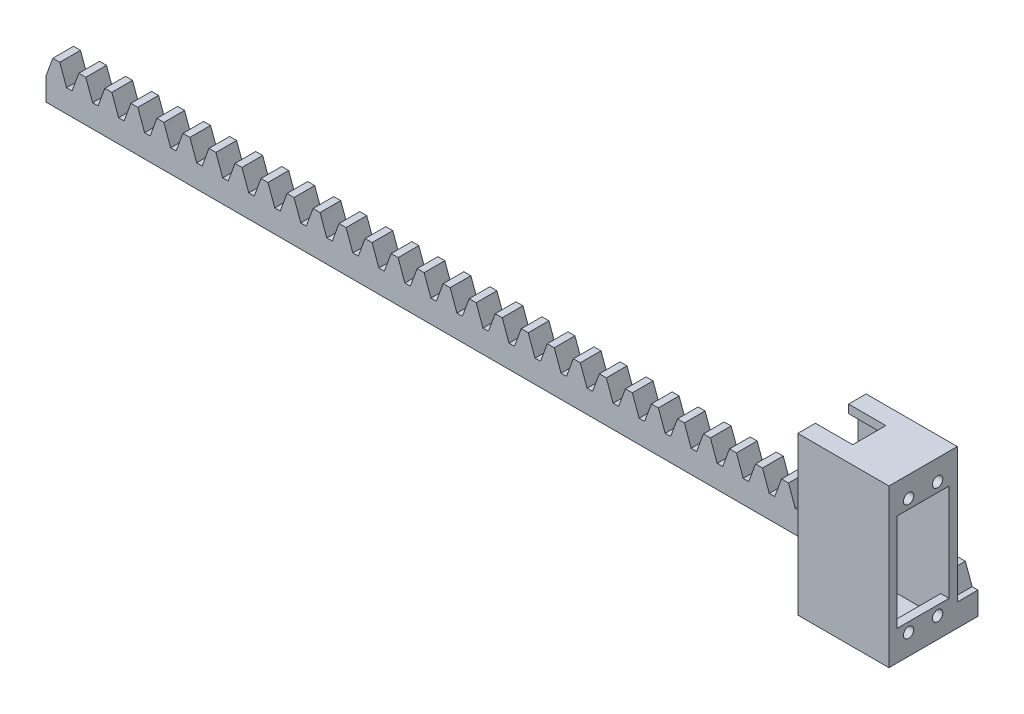
SolidWorks part; units mm, degrees
ref_plane "前视基准面" through (0, 0, 0) normal (0, 0, 1) x (1, 0, 0)
ref_plane "上视基准面" through (0, 0, 0) normal (0, 1, 0) x (1, 0, 0)
ref_plane "右视基准面" through (0, 0, 0) normal (1, 0, 0) x (0, 0, -1)
sketch "草图1" plane through (0, 0, 0) normal (0, 0, 1) x (1, 0, 0)
  line L1 (0, 0) -> (220, 0)
  line L2 (0, 0) -> (0, -5.5)
  line L3 (0, -5.5) -> (220, -5.5)
  line L4 (220, 0) -> (220, -5.5)
  dimension "D1" = 5.5
  dimension "L" = 220
extrude "拉伸1" add sketch "草图1" along normal blind 5
sketch "草图2" plane through (0, 0, 5) normal (0, 0, 1) x (1, 0, 0)
  line L0 (0, 0) -> (1.6379, 4.5)
  line L1 (1.6379, 4.5) -> (3.3236, 4.5)
  line L2 (3.3236, 4.5) -> (4.9614, 0)
  line L3 (220, 0) -> (0, 0) construction
  line L4 (0, 0) -> (4.9614, 0)
  line L5 (0.9099, 2.5) -> (4.0515, 2.5) construction
  dimension "D2" = 70
  dimension "alpha" = 110
  dimension "ha" = 2
  dimension "hf" = 2.5
  dimension "S" = 3.1416
extrude "拉伸2" add sketch "草图2" against normal up to surface (5 mm away) up to face at (110, -2.75, 0)
pattern_linear "阵列(线性)1" count 35 spacing 6.2832 along (1, 0, 0) of "拉伸2"
sketch "草图4" plane through (220, 0, 0) normal (1, 0, 0) x (0, 0, -1)
  line L0 (-5, -5.5) -> (-5, 0) construction
  line L1 (-5, -5.5) -> (-21.5, -5.5)
  line L2 (-5, -5.5) -> (-5, 32.5)
  line L3 (-5, 32.5) -> (-21.5, 32.5)
  line L4 (-21.5, -5.5) -> (-21.5, 32.5)
  line L6 (-21.5, 13.5) -> (-5, 13.5) construction
  line L7 (-13.25, 32.5) -> (-13.25, -5.5) construction
  line L8 (-5, -5.5) -> (0, -5.5) construction
  line L9 (-19.5, 25.25) -> (-7, 25.25)
  line L10 (-19.5, 25.25) -> (-19.5, 1.75)
  line L11 (-19.5, 1.75) -> (-7, 1.75)
  line L12 (-7, 25.25) -> (-7, 1.75)
  circle A0 centre (-16.75, 27.5) radius 1.25
  circle A1 centre (-9.75, 27.5) radius 1.25
  circle A2 centre (-9.75, -0.5) radius 1.25
  circle A3 centre (-16.75, -0.5) radius 1.25
  point P26 (-13.25, 25.25)
  point P27 (-7, 13.5)
  dimension "D3" = 2.5
  dimension "D4" = 7
  dimension "D5" = 28
  dimension "D1" = 16.5
  dimension "D2" = 38
  dimension "D6" = 23.5
  dimension "D7" = 12.5
extrude "凸台-拉伸1" add sketch "草图4" against normal blind 22
sketch "草图5" plane through (198, 0, 0) normal (-1, 0, 0) x (0, 0, 1)
  line L0 (7, 1.75) -> (7, 25.25) construction
  line L1 (7, 30.5) -> (19.5, 30.5)
  line L2 (7, 30.5) -> (7, -3.5)
  line L3 (7, -3.5) -> (19.5, -3.5)
  line L4 (19.5, 30.5) -> (19.5, -3.5)
  line L5 (5, 32.5) -> (21.5, 32.5) construction
  point P6 (7, 13.5)
  point P7 (7, 13.5)
  point P10 (13.25, 32.5)
  point P11 (13.25, 30.5)
  dimension "D1" = 12.5
  dimension "D2" = 34
extrude "切除-拉伸1" cut sketch "草图5" against normal blind 20
sketch "草图6" plane through (0, 32.5, 0) normal (0, 1, 0) x (1, 0, 0)
  line L0 (198, -5) -> (198, -21.5) construction
  line L1 (198, -9.25) -> (207, -9.25)
  line L2 (198, -9.25) -> (198, -17.25)
  line L3 (198, -17.25) -> (207, -17.25)
  line L4 (207, -9.25) -> (207, -17.25)
  line L5 (220, -5) -> (220, -21.5) construction
  point P8 (220, -13.25)
  point P9 (207, -13.25)
  dimension "D1" = 8
  dimension "D2" = 9
extrude "切除-拉伸2" cut sketch "草图6" against normal through all
equation "\"d\"=\"S@草图2\" * 2"
equation "\"z\"= int(  \"L@草图1\" / (  \"S@草图2\" * 2 ) + 0.5 )"
